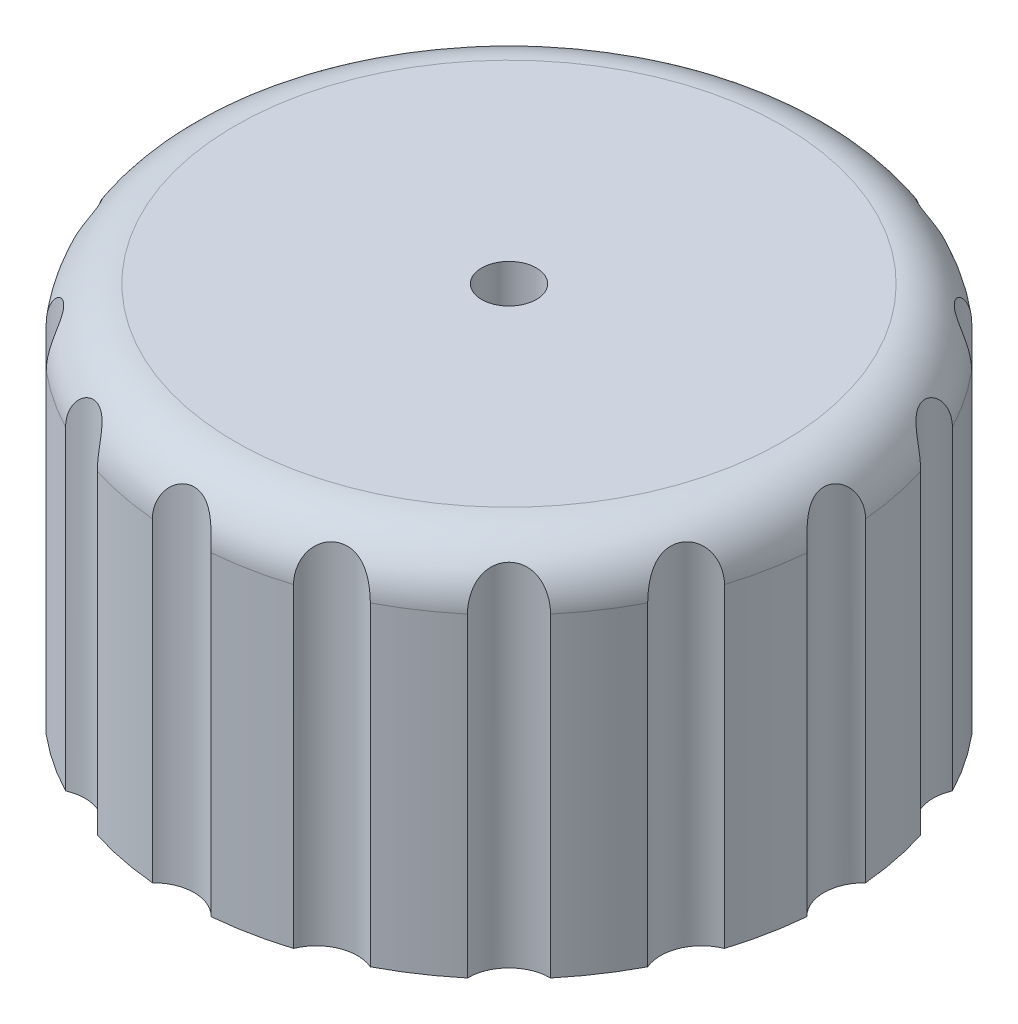
SolidWorks part; units mm, degrees
ref_plane "Front Plane" through (0, 0, 0) normal (0, 0, 1) x (1, 0, 0)
ref_plane "Top Plane" through (0, 0, 0) normal (0, 1, 0) x (1, 0, 0)
ref_plane "Right Plane" through (0, 0, 0) normal (1, 0, 0) x (0, 0, -1)
sketch "Sketch1" plane through (0, 0, 0) normal (0, 0, 1) x (1, 0, 0)
  line L0 (-2.765, 0) -> (-2.765, 2.8911)
  line L1 (-2.765, 2.8911) -> (0, 2.8911)
  line L2 (0, 2.8911) -> (0, 8)
  line L3 (0, 8) -> (-6, 8)
  line L4 (-6, 8) -> (-6, 1.2448)
  line L5 (-6, 1.2448) -> (-4.0034, 1.2448)
  line L6 (-4.0034, 1.2448) -> (-3.0676, 0)
  line L7 (-3.0676, 0) -> (-2.765, 0)
  dimension "D1" = 2.765
  dimension "D2" = 6
  dimension "D3" = 8
revolve "Revolve1" add sketch "Sketch1" angle 360 about L2
fillet "Fillet1" radius 1 1 edges at (0, 8, -6)
sketch "Sketch2" plane through (0, 0, 0) normal (0, 1, 0) x (1, 0, 0)
  circle A0 centre (0, 6.5) radius 0.75
  dimension "D2" = 1.5
  dimension "D1" = 6.5
extrude "Cut-Extrude1" cut sketch "Sketch2" along normal through all
pattern_circular "CirPattern1" count 16 over 360 about axis through (0, 0, 0) along (0, 1, 0) of "Cut-Extrude1"
sketch "Sketch3" plane through (0, 0, 0) normal (0, 1, 0) x (1, 0, 0)
  circle A0 centre (0, 0) radius 0.5
  point P2 (0, 0)
extrude "Cut-Extrude2" cut sketch "Sketch3" along normal through all
